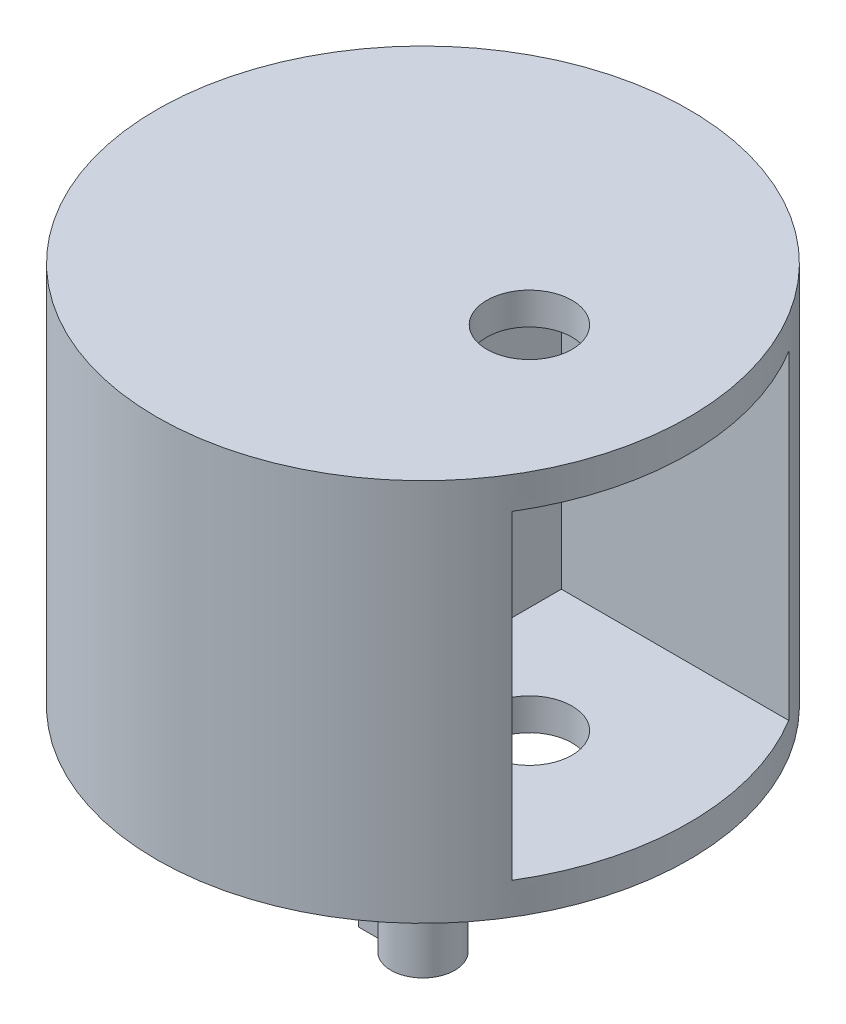
SolidWorks part; units mm, degrees
ref_plane "Front Plane" through (0, 0, 0) normal (0, 0, 1) x (1, 0, 0)
ref_plane "Top Plane" through (0, 0, 0) normal (0, 1, 0) x (1, 0, 0)
ref_plane "Right Plane" through (0, 0, 0) normal (1, 0, 0) x (0, 0, -1)
sketch "Sketch1" plane through (0, 0, 0) normal (0, 1, 0) x (1, 0, 0)
  circle A0 centre (0, 0) radius 12.5
  dimension "D1" = 25
extrude "Boss-Extrude1" add sketch "Sketch1" along normal blind 18
sketch "Sketch2" plane through (0, 0, 0) normal (1, 0, 0) x (0, 0, -1)
  line L0 (-12.5, 18) -> (-12.5, 0) construction
  line L1 (-6.5, 16.5) -> (6.5, 16.5)
  line L2 (-6.5, 16.5) -> (-6.5, 1.5)
  line L3 (-6.5, 1.5) -> (6.5, 1.5)
  line L4 (6.5, 16.5) -> (6.5, 1.5)
  line L5 (-6.5, 16.5) -> (6.5, 1.5) construction
  line L6 (-6.5, 1.5) -> (6.5, 16.5) construction
  point P0 (0, 9)
  dimension "D1" = 15
  dimension "D2" = 13
  dimension "D3" = 9
  dimension "D4" = 12.5
extrude "Cut-Extrude1" cut sketch "Sketch2" along normal blind 18
sketch "Sketch3" plane through (0, 0, 0) normal (0, -1, 0) x (1, 0, 0)
  circle A0 centre (5, 0) radius 2
  circle A1 centre (5, 0) radius 1
  point P4 (5.2961, 0)
  dimension "D2" = 4
  dimension "D3" = 2
  dimension "D1" = 5
extrude "Cut-Extrude2" cut sketch "Sketch3" against normal through all contours A1 | A0 A1
sketch "Sketch5" plane through (0, 0, 0) normal (0, -1, 0) x (1, 0, 0)
  line L1 (-1.4142, 0.5) -> (-2.5142, 0.5)
  line L3 (-1.4142, -0.5) -> (-2.5142, -0.5)
  line L4 (-2.5142, 0.5) -> (-2.5142, -0.5)
  arc A0 (-1.4142, -0.5) -> (-1.4142, 0.5) centre (0, 0) ccw
  point P3 (-1.5, 0)
  dimension "D1" = 3
  dimension "D2" = 1.1
  dimension "D3" = 1
extrude "Boss-Extrude2" add sketch "Sketch5" along normal blind 10
